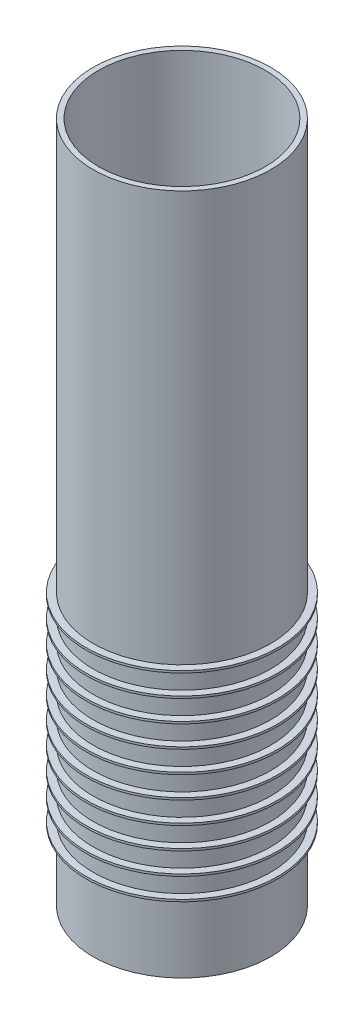
SolidWorks part; units mm, degrees
material "Polyetheretherketone (PEEK)"
ref_plane "Front Plane" through (0, 0, 0) normal (0, 0, 1) x (1, 0, 0)
ref_plane "Top Plane" through (0, 0, 0) normal (0, 1, 0) x (1, 0, 0)
ref_plane "Right Plane" through (0, 0, 0) normal (1, 0, 0) x (0, 0, -1)
sketch "Sketch1" plane through (0, 0, 0) normal (0, 1, 0) x (1, 0, 0)
  circle A0 centre (0, 0) radius 31.75
  dimension "D1" = 63.5
extrude "Boss-Extrude1" add sketch "Sketch1" along normal blind 243.84
ref_plane "Plane1" through (0, 25.4, 0) normal (0, 1, 0) x (1, 0, 0)
sketch "Sketch2" plane through (0, 25.4, 0) normal (0, 1, 0) x (1, 0, 0)
  circle A0 centre (0, 0) radius 34.29
  circle A1 centre (0, 0) radius 31.75 construction
  dimension "D1" = 68.58
extrude "Boss-Extrude2" add sketch "Sketch2" along normal blind 0.762
pattern_linear "LPattern1" count 10 spacing 7.874 along (0, 1, 0) of "Boss-Extrude2"
sketch "Sketch3" plane through (0, 243.84, 0) normal (0, 1, 0) x (1, 0, 0)
  circle A0 centre (0, 0) radius 29.845
  circle A1 centre (0, 0) radius 31.75 construction
  dimension "D1" = 59.69
extrude "Cut-Extrude1" cut sketch "Sketch3" against normal through all
